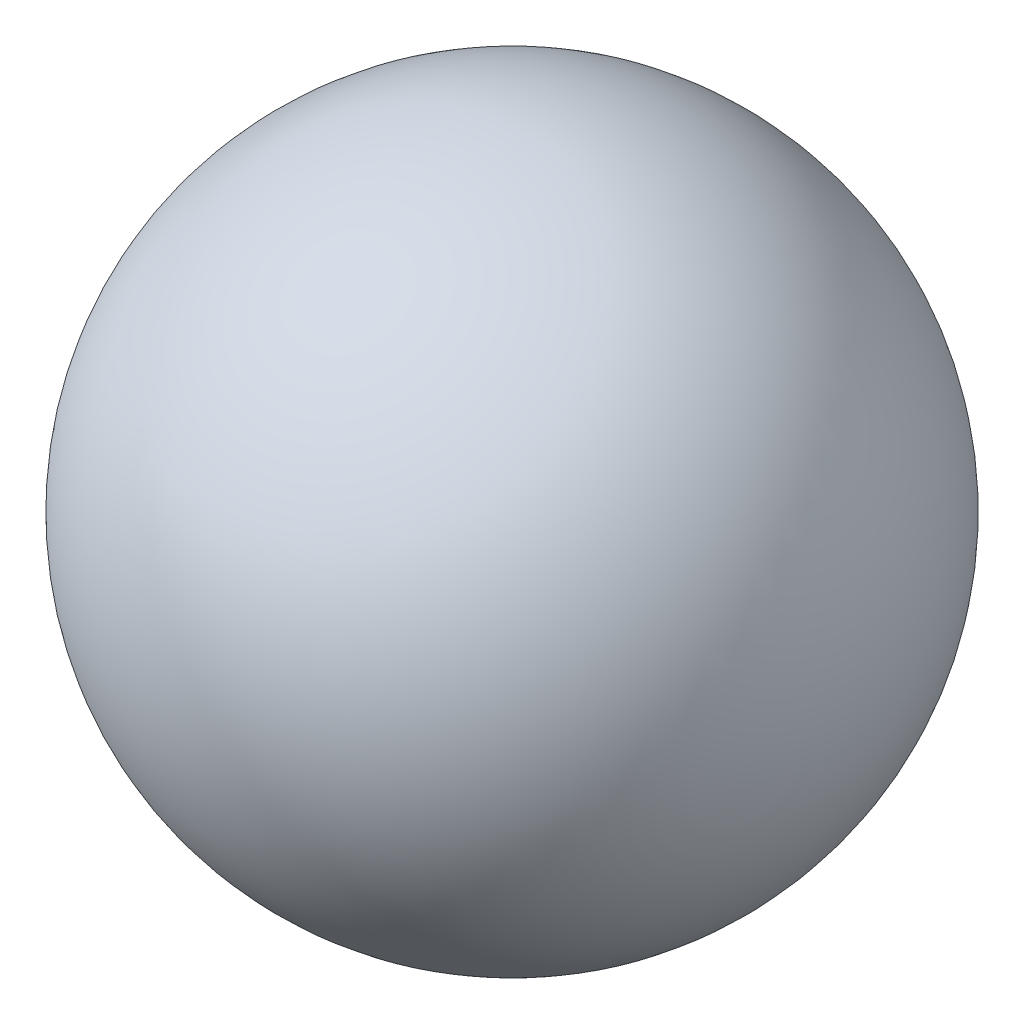
SolidWorks part; units mm, degrees
material "사용자정의 플라스틱"
ref_plane "정면" through (0, 0, 0) normal (0, 0, 1) x (1, 0, 0)
ref_plane "윗면" through (0, 0, 0) normal (0, 1, 0) x (1, 0, 0)
ref_plane "우측면" through (0, 0, 0) normal (1, 0, 0) x (0, 0, -1)
sketch "스케치1" plane through (0, 0, 0) normal (0, 0, 1) x (1, 0, 0)
  line L0 (0, 3.86) -> (0, -3.86) construction
  circle A0 centre (0, 0) radius 3.86
  dimension "D1" = 7.72
revolve "회전3" add sketch "스케치1" angle 360 about L0
